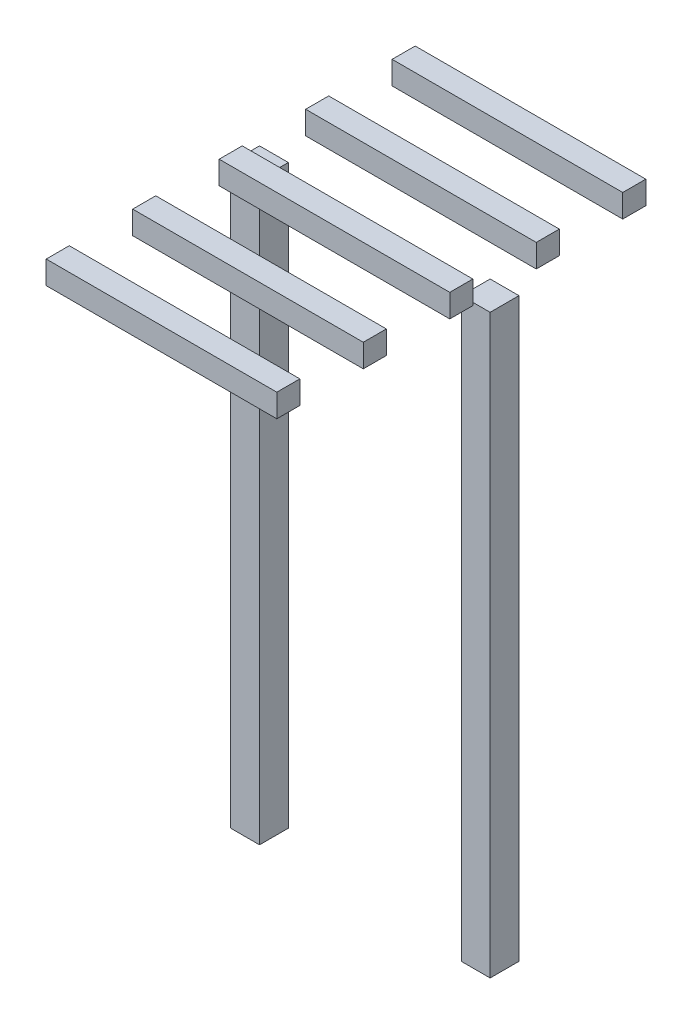
SolidWorks part; units mm, degrees
ref_plane "前视基准面" through (0, 0, 0) normal (0, 0, 1) x (1, 0, 0)
ref_plane "上视基准面" through (0, 0, 0) normal (0, 1, 0) x (1, 0, 0)
ref_plane "右视基准面" through (0, 0, 0) normal (1, 0, 0) x (0, 0, -1)
other "Configuration Table"
sketch "草图1" plane through (0, 0, 0) normal (0, 1, 0) x (1, 0, 0)
  line L1 (-450, 950) -> (-350, 950)
  line L2 (-450, 950) -> (-450, 1050)
  line L3 (-450, 1050) -> (-350, 1050)
  line L4 (-350, 950) -> (-350, 1050)
  line L5 (-450, 950) -> (-350, 1050) construction
  line L6 (-450, 1050) -> (-350, 950) construction
  point P0 (-400, 1000)
extrude "凸台-拉伸1" add sketch "草图1" along normal blind 2000
sketch "草图2" plane through (0, 0, 0) normal (0, 1, 0) x (1, 0, 0)
  line L1 (350, 950) -> (450, 950)
  line L2 (350, 950) -> (350, 1050)
  line L3 (350, 1050) -> (450, 1050)
  line L4 (450, 950) -> (450, 1050)
  line L5 (350, 950) -> (450, 1050) construction
  line L6 (350, 1050) -> (450, 950) construction
  point P0 (400, 1000)
extrude "凸台-拉伸2" add sketch "草图2" along normal blind 2000
sketch "草图3" plane through (0, 2000, 0) normal (0, 1, 0) x (1, 0, 0)
  line L1 (-400, 260) -> (400, 260)
  line L2 (-400, 260) -> (-400, 340)
  line L3 (-400, 340) -> (400, 340)
  line L4 (400, 260) -> (400, 340)
  line L5 (-400, 260) -> (400, 340) construction
  line L6 (-400, 340) -> (400, 260) construction
  point P0 (0, 300)
extrude "凸台-拉伸3" add sketch "草图3" along normal blind 80
sketch "草图4" plane through (0, 2000, 0) normal (0, 1, 0) x (1, 0, 0)
  line L1 (-400, 560) -> (400, 560)
  line L2 (-400, 560) -> (-400, 640)
  line L3 (-400, 640) -> (400, 640)
  line L4 (400, 560) -> (400, 640)
  line L5 (-400, 560) -> (400, 640) construction
  line L6 (-400, 640) -> (400, 560) construction
  point P0 (0, 600)
extrude "凸台-拉伸4" add sketch "草图4" along normal blind 80
sketch "草图5" plane through (0, 2000, 0) normal (0, 1, 0) x (1, 0, 0)
  line L1 (-400, 860) -> (400, 860)
  line L2 (-400, 860) -> (-400, 940)
  line L3 (-400, 940) -> (400, 940)
  line L4 (400, 860) -> (400, 940)
  line L5 (-400, 860) -> (400, 940) construction
  line L6 (-400, 940) -> (400, 860) construction
  point P0 (0, 900)
extrude "凸台-拉伸5" add sketch "草图5" along normal blind 80
sketch "草图6" plane through (0, 2000, 0) normal (0, 1, 0) x (1, 0, 0)
  line L1 (-400, 1160) -> (400, 1160)
  line L2 (-400, 1160) -> (-400, 1240)
  line L3 (-400, 1240) -> (400, 1240)
  line L4 (400, 1160) -> (400, 1240)
  line L5 (-400, 1160) -> (400, 1240) construction
  line L6 (-400, 1240) -> (400, 1160) construction
  point P0 (0, 1200)
extrude "凸台-拉伸6" add sketch "草图6" along normal blind 80
sketch "草图7" plane through (0, 2000, 0) normal (0, 1, 0) x (1, 0, 0)
  line L1 (-400, 1460) -> (400, 1460)
  line L2 (-400, 1460) -> (-400, 1540)
  line L3 (-400, 1540) -> (400, 1540)
  line L4 (400, 1460) -> (400, 1540)
  line L5 (-400, 1460) -> (400, 1540) construction
  line L6 (-400, 1540) -> (400, 1460) construction
  point P0 (0, 1500)
extrude "凸台-拉伸7" add sketch "草图7" along normal blind 80
